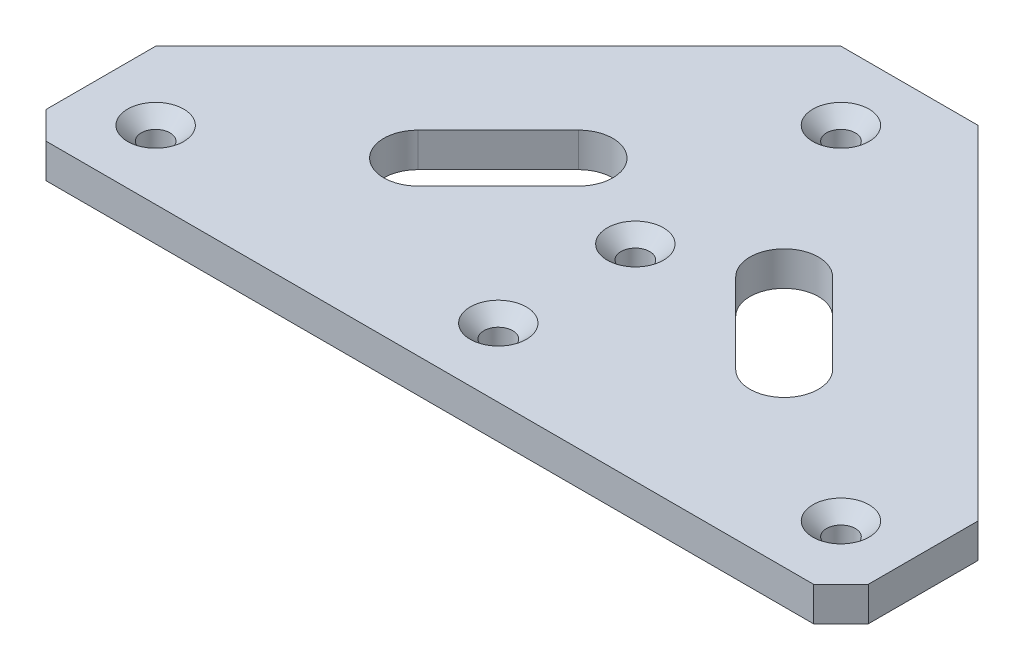
SolidWorks part; units mm, degrees
ref_plane "前视基准面" through (0, 0, 0) normal (0, 0, 1) x (1, 0, 0)
ref_plane "上视基准面" through (0, 0, 0) normal (0, 1, 0) x (1, 0, 0)
ref_plane "右视基准面" through (0, 0, 0) normal (1, 0, 0) x (0, 0, -1)
sketch "草图2" plane through (0, 0, 0) normal (0, 1, 0) x (1, 0, 0)
  line L0 (0, 0) -> (0, -19070.1747) construction
  line L1 (0, 35) -> (-10, 35)
  line L2 (-10, 35) -> (-60, -15)
  line L3 (-60, -15) -> (-60, -35)
  line L4 (-60, -35) -> (60, -35)
  line L5 (-50, -25) -> (0, -25) construction
  line L6 (10, 35) -> (60, -15)
  line L7 (60, -15) -> (60, -35)
  line L8 (0, 35) -> (10, 35)
  circle A0 centre (-50, -25) radius 2.1
  circle A1 centre (0, 25) radius 2.1
  circle A2 centre (0, -5) radius 2.1
  circle A3 centre (0, -25) radius 2.1
  circle A4 centre (50, -25) radius 2.1
  point P21 (0, -35)
  dimension "D6" = 4.2
  dimension "D7" = 10
  dimension "D9" = 20
  dimension "D10" = 10
  dimension "D1" = 20
  dimension "D2" = 120
  dimension "D3" = 70
  dimension "D4" = 20
  dimension "D5" = 35
  dimension "D8" = 10
extrude "凸台-拉伸1" add sketch "草图2" along normal mid plane 5
chamfer "倒角1" distance 2 angle 45 5 edges at (-50, 2.5, 27.1) (50, 2.5, 22.9) (0, 2.5, 27.1) (0, 2.5, 7.1) (0, 2.5, -22.9)
chamfer "倒角2" distance 4 angle 45 2 edges at (60, 0, 35) (-60, 0, 35)
sketch "草图3" plane through (0, 2.5, 0) normal (0, 1, 0) x (1, 0, 0)
  line L0 (-26.7157, -10) -> (-15, 1.7157) construction
  line L1 (-30.2513, -6.4645) -> (-18.5355, 5.2513)
  line L2 (-23.1802, -13.5355) -> (-11.4645, -1.8198)
  line L3 (-10, 35) -> (-60, -15) construction
  line L4 (0, 25) -> (0, -25) construction
  line L5 (26.7157, -10) -> (15, 1.7157) construction
  line L6 (30.2513, -6.4645) -> (18.5355, 5.2513)
  line L7 (23.1802, -13.5355) -> (11.4645, -1.8198)
  arc A0 (-30.2513, -6.4645) -> (-23.1802, -13.5355) centre (-26.7157, -10) ccw
  arc A1 (-11.4645, -1.8198) -> (-18.5355, 5.2513) centre (-15, 1.7157) ccw
  circle A2 centre (-50, -25) radius 2.1 construction
  circle A3 centre (0, -5) radius 2.1 construction
  arc A4 (30.2513, -6.4645) -> (23.1802, -13.5355) centre (26.7157, -10) cw
  arc A5 (11.4645, -1.8198) -> (18.5355, 5.2513) centre (15, 1.7157) cw
  point P2 (-20.8579, -4.1421)
  point P19 (20.8579, -4.1421)
  dimension "D2" = 5
  dimension "D3" = 15
  dimension "D1" = 15
  dimension "D4" = 15
extrude "切除-拉伸1" cut sketch "草图3" against normal through all
